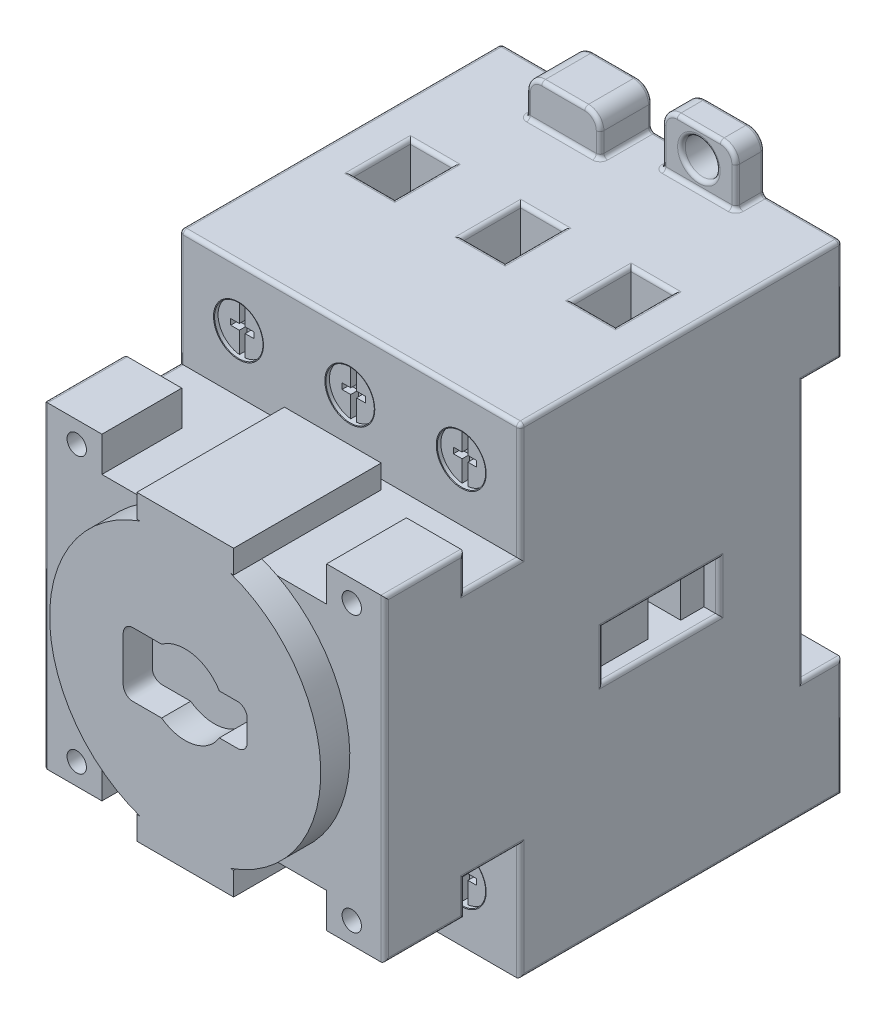
SolidWorks part; units mm, degrees
ref_plane "Front" through (0, 0, 0) normal (0, 0, 1) x (1, 0, 0)
ref_plane "Top" through (0, 0, 0) normal (0, 1, 0) x (1, 0, 0)
ref_plane "Right" through (0, 0, 0) normal (1, 0, 0) x (0, 0, -1)
sketch "Sketch1" plane through (0, 0, 0) normal (0, 0, 1) x (1, 0, 0)
  line L1 (-22.352, -31.496) -> (22.352, -31.496)
  line L2 (-22.352, -31.496) -> (-22.352, 31.496)
  line L3 (-22.352, 31.496) -> (22.352, 31.496)
  line L4 (22.352, -31.496) -> (22.352, 31.496)
  line L5 (-22.352, -31.496) -> (22.352, 31.496) construction
  line L6 (-22.352, 31.496) -> (22.352, -31.496) construction
  point P0 (0, 0)
  dimension "D1" = 44.704
  dimension "D2" = 62.992
extrude "Boss-Extrude1" add sketch "Sketch1" along normal blind 60
sketch "Sketch6" plane through (0, 0, 0) normal (0, 0, -1) x (-1, 0, 0)
  line L0 (-22.352, -31.496) -> (-22.352, 31.496) construction
  line L1 (-22.352, 18.034) -> (22.352, 18.034)
  line L2 (-22.352, 18.034) -> (-22.352, -16.002)
  line L3 (-22.352, -16.002) -> (22.352, -16.002)
  line L4 (22.352, 18.034) -> (22.352, -16.002)
  line L5 (22.352, 31.496) -> (22.352, -31.496) construction
  line L6 (-22.352, 31.496) -> (22.352, 31.496) construction
  dimension "D1" = 13.462
  dimension "D2" = 34.036
extrude "Cut-Extrude5" cut sketch "Sketch6" against normal blind 5.08
sketch "Sketch3" plane through (0, 0, 60) normal (0, 0, 1) x (1, 0, 0)
  line L0 (-22.352, 31.496) -> (-22.352, -31.496) construction
  line L1 (22.352, 20.828) -> (-22.352, 20.828)
  line L2 (22.352, 20.828) -> (22.352, 31.496)
  line L3 (22.352, 31.496) -> (-22.352, 31.496)
  line L4 (-22.352, 20.828) -> (-22.352, 31.496)
  line L5 (-22.352, -31.496) -> (22.352, -31.496)
  line L6 (-22.352, -31.496) -> (-22.352, -20.828)
  line L7 (-22.352, -20.828) -> (22.352, -20.828)
  line L8 (22.352, -31.496) -> (22.352, -20.828)
  line L9 (22.352, -31.496) -> (22.352, 31.496) construction
  dimension "D1" = 10.668
  dimension "D2" = 41.656
extrude "Cut-Extrude2" cut sketch "Sketch3" against normal blind 17.78
sketch "Sketch4" plane through (0, 0, 60) normal (0, 0, 1) x (1, 0, 0)
  line L1 (0, 0) -> (0, 0.508) construction
  circle A0 centre (0, 0.508) radius 17.78
  dimension "D1" = 35.56
  dimension "D2" = 0.508
extrude "Boss-Extrude2" add sketch "Sketch4" along normal blind 3.81
sketch "Sketch5" plane through (0, 0, 60) normal (0, 0, 1) x (1, 0, 0)
  line L0 (-22.352, 20.828) -> (22.352, 20.828) construction
  line L1 (-14.732, 16.256) -> (14.732, 16.256)
  line L2 (-14.732, 16.256) -> (-14.732, 20.828)
  line L3 (-14.732, 20.828) -> (14.732, 20.828)
  line L4 (14.732, 16.256) -> (14.732, 20.828)
  line L6 (0, 0) -> (0, 16.256) construction
  line L7 (22.352, -20.828) -> (-22.352, -20.828) construction
  line L8 (14.73, -20.828) -> (-14.73, -20.828)
  line L9 (14.73, -20.828) -> (14.73, -16.258)
  line L10 (14.73, -16.258) -> (-14.73, -16.258)
  line L11 (-14.73, -20.828) -> (-14.73, -16.258)
  line L12 (0, 0) -> (0, -16.258) construction
  dimension "D1" = 29.464
  dimension "D2" = 4.572
  dimension "D3" = 29.46
  dimension "D4" = 4.57
extrude "Cut-Extrude3" cut sketch "Sketch5" against normal blind 17.78
sketch "Sketch7" plane through (0, 0, 63.81) normal (0, 0, 1) x (1, 0, 0)
  line L0 (-5.9186, -16.258) -> (-14.73, -16.258) construction
  line L1 (-6.35, 20.32) -> (6.35, 20.32)
  line L2 (-6.35, 20.32) -> (-6.35, 17.272)
  line L3 (-6.35, 17.272) -> (6.35, 17.272)
  line L4 (6.35, 20.32) -> (6.35, 17.272)
  line L5 (6.35, -19.304) -> (-6.35, -19.304)
  line L6 (6.35, -19.304) -> (6.35, -16.258)
  line L7 (6.35, -16.258) -> (-6.35, -16.258)
  line L8 (-6.35, -19.304) -> (-6.35, -16.258)
  line L10 (0, 0) -> (0, 17.272) construction
  line L11 (0, 0) -> (0, -16.258) construction
  dimension "D1" = 3.048
  dimension "D2" = 3.046
  dimension "D3" = 12.7
  dimension "D4" = 12.7
  dimension "D5" = 17.272
extrude "Boss-Extrude3" add sketch "Sketch7" against normal up to surface (21.59 mm away) up to face at (0, 22.352, 42.22)
sketch "Sketch8" plane through (0, 20.828, 0) normal (0, 1, 0) x (1, 0, 0)
  line L0 (-22.352, -42.22) -> (-22.352, -60) construction
  line L1 (-22.352, -49.53) -> (-14.732, -49.53)
  line L2 (-22.352, -49.53) -> (-22.352, -42.22)
  line L3 (-22.352, -42.22) -> (-14.732, -42.22)
  line L4 (-14.732, -49.53) -> (-14.732, -42.22)
  line L7 (22.352, -49.53) -> (14.732, -49.53)
  line L8 (22.352, -49.53) -> (22.352, -42.22)
  line L9 (22.352, -42.22) -> (14.732, -42.22)
  line L10 (14.732, -49.53) -> (14.732, -42.22)
  line L12 (6.35, -44.45) -> (-6.35, -44.45)
  line L13 (6.35, -44.45) -> (6.35, -42.22)
  line L14 (6.35, -42.22) -> (-6.35, -42.22)
  line L15 (-6.35, -44.45) -> (-6.35, -42.22)
  line L16 (6.35, -42.22) -> (6.35, -63.81) construction
  line L17 (22.352, -42.22) -> (22.352, 0) construction
  dimension "D1" = 7.31
  dimension "D2" = 2.23
  dimension "D3" = 7.31
extrude "Cut-Extrude6" cut sketch "Sketch8" against normal up to surface (4.572 mm away) up to face at (0, 16.256, 54.0733)
sketch "Sketch9" plane through (0, 0, 63.81) normal (0, 0, 1) x (1, 0, 0)
  line L10 (-5.9186, -16.258) -> (-6.35, -16.258)
  line L11 (-6.35, -16.258) -> (-6.35, -19.304)
  line L12 (-6.35, -19.304) -> (6.35, -19.304)
  line L13 (6.35, -19.304) -> (6.35, -16.258)
  line L14 (6.35, -16.258) -> (5.9186, -16.258)
  line L15 (5.9242, 17.272) -> (6.35, 17.272)
  line L16 (6.35, 17.272) -> (6.35, 20.32)
  line L17 (6.35, 20.32) -> (-6.35, 20.32)
  line L18 (-6.35, 20.32) -> (-6.35, 17.272)
  line L19 (-6.35, 17.272) -> (-5.9242, 17.272)
  line L20 (-5.9186, -16.258) -> (-6.35, -16.258)
  line L21 (-6.35, -16.258) -> (-6.35, -19.304)
  line L22 (-6.35, -19.304) -> (6.35, -19.304)
  line L23 (6.35, -19.304) -> (6.35, -16.258)
  line L24 (6.35, -16.258) -> (5.9186, -16.258)
  line L25 (5.9242, 17.272) -> (6.35, 17.272)
  line L26 (6.35, 17.272) -> (6.35, 20.32)
  line L27 (6.35, 20.32) -> (-6.35, 20.32)
  line L28 (-6.35, 20.32) -> (-6.35, 17.272)
  line L29 (-6.35, 17.272) -> (-5.9242, 17.272)
  arc A2 (-5.9242, 17.272) -> (-5.9186, -16.258) centre (0, 0.508) ccw
  arc A3 (5.9186, -16.258) -> (5.9242, 17.272) centre (0, 0.508) ccw
  arc A4 (-5.9242, 17.272) -> (-5.9186, -16.258) centre (0, 0.508) ccw
  arc A5 (5.9186, -16.258) -> (5.9242, 17.272) centre (0, 0.508) ccw
  arc A6 (-3.09, -3.683) -> (4.4721, -2.159) centre (0, 0.508) ccw
  arc A7 (4.4721, 3.175) -> (-3.09, 4.699) centre (0, 0.508) ccw
  spline S2 degree 3 poles (-3.09, 4.699) (-4.346, 4.699) (-5.602, 4.699) (-6.858, 4.699) (-7.6019, 4.699) (-8.128, 4.1729) (-8.128, 3.429) (-8.128, 1.4817) (-8.128, -0.4657) (-8.128, -2.413) (-8.128, -3.1569) (-7.6019, -3.683) (-6.858, -3.683) (-5.602, -3.683) (-4.346, -3.683) (-3.09, -3.683) knots 0.43328 0.43328 0.43328 0.43328 0.519787 0.519787 0.519787 0.561023 0.561023 0.561023 0.695148 0.695148 0.695148 0.736383 0.736383 0.736383 0.822891 0.822891 0.822891 0.822891 weights 1 1 1 1 0.804738 0.804738 1 1 1 1 0.804738 0.804738 1 1 1 1
  spline S3 degree 3 poles (4.4721, -2.159) (5.2674, -2.159) (6.0627, -2.159) (6.858, -2.159) (7.6019, -2.159) (8.128, -1.6329) (8.128, -0.889) (8.128, 0.0423) (8.128, 0.9737) (8.128, 1.905) (8.128, 2.6489) (7.6019, 3.175) (6.858, 3.175) (6.0627, 3.175) (5.2674, 3.175) (4.4721, 3.175) knots 0 0 0 0 0.054777 0.054777 0.054777 0.096012 0.096012 0.096012 0.160159 0.160159 0.160159 0.201394 0.201394 0.201394 0.256171 0.256171 0.256171 0.256171 weights 1 1 1 1 0.804738 0.804738 1 1 1 1 0.804738 0.804738 1 1 1 1
  dimension "D1" = 0
extrude "Cut-Extrude7" cut sketch "Sketch9" against normal up to surface (3.81 mm away) contours A6 S3 A7 S2 up to face at (14.9776, -1.8919, 60)
sketch "Sketch10" plane through (0, 0, 0) normal (0, 0, -1) x (-1, 0, 0)
  line L0 (-22.352, 31.496) -> (22.352, 31.496) construction
  line L1 (-12.192, 31.496) -> (-2.54, 31.496)
  line L2 (-12.192, 31.496) -> (-12.192, 38.608)
  line L3 (-12.192, 38.608) -> (-2.54, 38.608)
  line L4 (-2.54, 31.496) -> (-2.54, 38.608)
  line L7 (2.54, 36.576) -> (12.192, 36.576)
  line L8 (2.54, 36.576) -> (2.54, 31.496)
  line L9 (2.54, 31.496) -> (12.192, 31.496)
  line L10 (12.192, 36.576) -> (12.192, 31.496)
  line L11 (22.352, -31.496) -> (-22.352, -31.496) construction
  line L12 (12.7, -38.608) -> (3.048, -38.608)
  line L13 (12.7, -38.608) -> (12.7, -31.496)
  line L14 (12.7, -31.496) -> (3.048, -31.496)
  line L15 (3.048, -38.608) -> (3.048, -31.496)
  line L17 (-22.352, 18.034) -> (-22.352, 31.496) construction
  line L18 (-22.352, -31.496) -> (-22.352, -16.002) construction
  dimension "D1" = 10.16
  dimension "D2" = 9.652
  dimension "D3" = 5.08
  dimension "D4" = 9.652
  dimension "D5" = 7.112
  dimension "D6" = 5.08
  dimension "D7" = 25.4
  dimension "D8" = 9.652
  dimension "D9" = 7.112
extrude "Boss-Extrude4" add sketch "Sketch10" against normal blind 6.858
sketch "Sketch11" plane through (0, 0, 6.858) normal (0, 0, 1) x (1, 0, 0)
  line L0 (12.192, 31.496) -> (12.192, 38.608) construction
  line L1 (12.192, 38.608) -> (2.54, 38.608) construction
  line L2 (2.54, 38.608) -> (2.54, 31.496) construction
  line L3 (2.54, 31.496) -> (12.192, 31.496) construction
  line L4 (-12.7, -31.496) -> (-12.7, -38.608) construction
  line L5 (-12.7, -38.608) -> (-3.048, -38.608) construction
  line L6 (-3.048, -38.608) -> (-3.048, -31.496) construction
  line L7 (-3.048, -31.496) -> (-12.7, -31.496) construction
  line L8 (12.192, 31.496) -> (12.192, 38.608)
  line L9 (12.192, 38.608) -> (2.54, 38.608)
  line L10 (2.54, 38.608) -> (2.54, 31.496)
  line L11 (2.54, 31.496) -> (12.192, 31.496)
  line L12 (-12.7, -31.496) -> (-12.7, -38.608)
  line L13 (-12.7, -38.608) -> (-3.048, -38.608)
  line L14 (-3.048, -38.608) -> (-3.048, -31.496)
  line L15 (-3.048, -31.496) -> (-12.7, -31.496)
extrude "Cut-Extrude8" cut sketch "Sketch11" against normal offset from surface (3.048 mm away) 3.81 up to face at (1.0583, 31.2843, 0)
sketch "Sketch12" plane through (0, 0, 0) normal (0, 0, -1) x (-1, 0, 0)
  circle A0 centre (-7.366, 35.052) radius 2.286
  circle A1 centre (7.874, -35.052) radius 2.286
  dimension "D1" = 4.572
  dimension "D2" = 4.572
  dimension "D3" = 35.052
  dimension "D4" = 7.366
  dimension "D5" = 7.874
  dimension "D6" = 35.052
extrude "Cut-Extrude9" cut sketch "Sketch12" against normal through all
sketch "Sketch14" plane through (0, 0, 42.22) normal (0, 0, 1) x (1, 0, 0)
  line L60 (-14.224, -23.368) -> (-14.224, -20.5969)
  line L61 (-13.081, -23.368) -> (-14.224, -23.368)
  line L62 (-13.081, -24.13) -> (-13.081, -23.368)
  line L63 (-14.224, -24.13) -> (-13.081, -24.13)
  line L64 (-14.224, -26.9011) -> (-14.224, -24.13)
  line L65 (-14.986, -24.13) -> (-14.986, -26.9011)
  line L66 (-16.129, -24.13) -> (-14.986, -24.13)
  line L67 (-16.129, -23.368) -> (-16.129, -24.13)
  line L68 (-14.986, -23.368) -> (-16.129, -23.368)
  line L69 (-14.986, -20.5969) -> (-14.986, -23.368)
  line L70 (0.381, -23.368) -> (0.381, -20.5969)
  line L71 (1.524, -23.368) -> (0.381, -23.368)
  line L72 (1.524, -24.13) -> (1.524, -23.368)
  line L73 (0.381, -24.13) -> (1.524, -24.13)
  line L74 (0.381, -26.9011) -> (0.381, -24.13)
  line L75 (-0.381, -24.13) -> (-0.381, -26.9011)
  line L76 (-1.524, -24.13) -> (-0.381, -24.13)
  line L77 (-1.524, -23.368) -> (-1.524, -24.13)
  line L78 (-0.381, -23.368) -> (-1.524, -23.368)
  line L79 (-0.381, -20.5969) -> (-0.381, -23.368)
  line L80 (14.986, -24.13) -> (14.986, -26.9011)
  line L81 (16.129, -24.13) -> (14.986, -24.13)
  line L82 (16.129, -23.368) -> (16.129, -24.13)
  line L83 (14.986, -23.368) -> (16.129, -23.368)
  line L84 (14.986, -20.5969) -> (14.986, -23.368)
  line L85 (14.224, -23.368) -> (14.224, -20.5969)
  line L86 (13.081, -23.368) -> (14.224, -23.368)
  line L87 (13.081, -24.13) -> (13.081, -23.368)
  line L88 (14.224, -24.13) -> (13.081, -24.13)
  line L89 (14.224, -26.9011) -> (14.224, -24.13)
  line L90 (14.986, 24.13) -> (14.986, 26.9011)
  line L91 (16.129, 24.13) -> (14.986, 24.13)
  line L92 (16.129, 23.368) -> (16.129, 24.13)
  line L93 (14.986, 23.368) -> (16.129, 23.368)
  line L94 (14.986, 20.5969) -> (14.986, 23.368)
  line L95 (14.224, 23.368) -> (14.224, 20.5969)
  line L96 (13.081, 23.368) -> (14.224, 23.368)
  line L97 (13.081, 24.13) -> (13.081, 23.368)
  line L98 (14.224, 24.13) -> (13.081, 24.13)
  line L99 (14.224, 26.9011) -> (14.224, 24.13)
  line L100 (0.381, 23.368) -> (0.381, 20.5969)
  line L101 (1.524, 23.368) -> (0.381, 23.368)
  line L102 (1.524, 24.13) -> (1.524, 23.368)
  line L103 (0.381, 24.13) -> (1.524, 24.13)
  line L104 (0.381, 26.9011) -> (0.381, 24.13)
  line L105 (-0.381, 24.13) -> (-0.381, 26.9011)
  line L106 (-1.524, 24.13) -> (-0.381, 24.13)
  line L107 (-1.524, 23.368) -> (-1.524, 24.13)
  line L108 (-0.381, 23.368) -> (-1.524, 23.368)
  line L109 (-0.381, 20.5969) -> (-0.381, 23.368)
  line L110 (-14.224, 23.368) -> (-14.224, 20.5969)
  line L111 (-13.081, 23.368) -> (-14.224, 23.368)
  line L112 (-13.081, 24.13) -> (-13.081, 23.368)
  line L113 (-14.224, 24.13) -> (-13.081, 24.13)
  line L114 (-14.224, 26.9011) -> (-14.224, 24.13)
  line L115 (-14.986, 24.13) -> (-14.986, 26.9011)
  line L116 (-16.129, 24.13) -> (-14.986, 24.13)
  line L117 (-16.129, 23.368) -> (-16.129, 24.13)
  line L118 (-14.986, 23.368) -> (-16.129, 23.368)
  line L119 (-14.986, 20.5969) -> (-14.986, 23.368)
  line L128 (22.352, -31.496) -> (22.352, 31.496)
  line L129 (22.352, 31.496) -> (-22.352, 31.496)
  line L130 (-22.352, 31.496) -> (-22.352, -31.496)
  line L131 (-22.352, -31.496) -> (22.352, -31.496)
  arc A12 (-17.78, -23.749) -> (-11.43, -23.749) centre (-14.605, -23.749) ccw
  arc A13 (-11.43, -23.749) -> (-17.78, -23.749) centre (-14.605, -23.749) ccw
  arc A14 (-3.175, -23.749) -> (3.175, -23.749) centre (0, -23.749) ccw
  arc A15 (3.175, -23.749) -> (-3.175, -23.749) centre (0, -23.749) ccw
  arc A16 (11.43, -23.749) -> (17.78, -23.749) centre (14.605, -23.749) ccw
  arc A17 (17.78, -23.749) -> (11.43, -23.749) centre (14.605, -23.749) ccw
  arc A18 (11.43, 23.749) -> (17.78, 23.749) centre (14.605, 23.749) ccw
  arc A19 (17.78, 23.749) -> (11.43, 23.749) centre (14.605, 23.749) ccw
  arc A20 (-3.175, 23.749) -> (3.175, 23.749) centre (0, 23.749) ccw
  arc A21 (3.175, 23.749) -> (-3.175, 23.749) centre (0, 23.749) ccw
  arc A22 (-17.78, 23.749) -> (-11.43, 23.749) centre (-14.605, 23.749) ccw
  arc A23 (-11.43, 23.749) -> (-17.78, 23.749) centre (-14.605, 23.749) ccw
  line M10 (-14.73, -16.258) -> (-14.73, -20.828)
  line M11 (-14.73, -20.828) -> (-22.352, -20.828)
  line M15 (22.352, -20.828) -> (14.73, -20.828)
  line M16 (14.73, -20.828) -> (14.73, -16.258)
extrude "Cut-Extrude11" cut sketch "Sketch14" against normal blind 1.5 contours L114 A23 L115 L116 L117 L118 L119 A22 L110 L111 L112 L113 | L104 A21 L105 L106 L107 L108 L109 A20 L100 L101 L102 L103 | L90 A19 L99 L98 L97 L96 L95 A18 L94 L93 L92 L91 | A17 L85 L86 L87 L88 L89 A16 L80 L81 L82 L83 L84 M16 M15 | L70 A15 L79 L78 L77 L76 L75 A14 L74 L73 L72 L71 | L60 A13 L69 L68 L67 L66 L65 A12 L64 L63 L62 L61 M10 M11
sketch "Sketch15" plane through (0, -20.828, 0) normal (0, -1, 0) x (1, 0, 0)
  line L1 (14.73, 42.22) -> (14.73, 60) construction
  line L2 (22.352, 42.22) -> (14.73, 42.22)
  line L3 (22.352, 42.22) -> (22.352, 49.53)
  line L4 (22.352, 49.53) -> (14.73, 49.53)
  line L7 (-14.73, 40.72) -> (-14.73, 60) construction
  line L8 (-22.352, 42.22) -> (-14.73, 42.22)
  line L9 (-22.352, 42.22) -> (-22.352, 49.53)
  line L10 (-22.352, 49.53) -> (-14.73, 49.53)
  line L13 (-6.35, 42.22) -> (-6.35, 60) construction
  line L14 (6.35, 42.22) -> (-6.35, 42.22)
  line L15 (6.35, 42.22) -> (6.35, 44.25)
  line L16 (6.35, 44.25) -> (-6.35, 44.25)
  line L19 (-14.73, 42.22) -> (-14.73, 49.53)
  line L20 (14.73, 42.22) -> (14.73, 49.53)
  line L21 (-6.35, 42.22) -> (-6.35, 44.25)
  dimension "D1" = 2.03
  dimension "D2" = 7.31
  dimension "D3" = 7.31
extrude "Cut-Extrude12" cut sketch "Sketch15" against normal up to surface (4.57 mm away) up to face at (10.54, -16.258, 51.11)
sketch "Sketch13" plane through (0, 0, 60) normal (0, 0, 1) x (1, 0, 0)
  line L0 (-22.352, 18.034) -> (22.352, 18.034) construction
  line L2 (-18.034, 18.034) -> (18.034, 18.034) construction
  line L3 (0, 0) -> (0, 18.034) construction
  line L4 (-18.034, -18.034) -> (18.034, -18.034) construction
  line L5 (0, -18.034) -> (0, 0) construction
  circle A0 centre (-18.034, 18.034) radius 1.27
  circle A1 centre (18.034, 18.034) radius 1.27
  circle A2 centre (18.034, -18.034) radius 1.27
  circle A3 centre (-18.034, -18.034) radius 1.27
  dimension "D1" = 2.54
  dimension "D2" = 2.54
  dimension "D3" = 2.54
  dimension "D4" = 2.54
  dimension "D5" = 36.068
  dimension "D6" = 36.068
  dimension "D7" = 18.034
extrude "Cut-Extrude10" cut sketch "Sketch13" against normal up to next
sketch "Sketch16" plane through (0, -31.496, 0) normal (0, -1, 0) x (1, 0, 0)
  line L0 (-22.352, 0) -> (-12.7, 0) construction
  line L1 (11.684, 24.638) -> (17.272, 24.638)
  line L2 (11.684, 24.638) -> (11.684, 17.018)
  line L3 (11.684, 17.018) -> (17.272, 17.018)
  line L4 (17.272, 24.638) -> (17.272, 17.018)
  line L5 (-2.794, 24.638) -> (2.794, 24.638)
  line L6 (-2.794, 24.638) -> (-2.794, 17.018)
  line L7 (-2.794, 17.018) -> (2.794, 17.018)
  line L8 (2.794, 24.638) -> (2.794, 17.018)
  line L9 (-17.272, 24.638) -> (-11.684, 24.638)
  line L10 (-17.272, 24.638) -> (-17.272, 17.018)
  line L11 (-17.272, 17.018) -> (-11.684, 17.018)
  line L12 (-11.684, 24.638) -> (-11.684, 17.018)
  line L13 (-3.048, 0) -> (22.352, 0) construction
  line L14 (-22.352, 42.22) -> (-22.352, 0) construction
  point P22 (-22.352, 21.11)
  dimension "D1" = 17.018
  dimension "D2" = 17.018
  dimension "D3" = 17.018
  dimension "D4" = 5.08
  dimension "D5" = 7.62
  dimension "D6" = 7.62
  dimension "D7" = 7.62
  dimension "D8" = 5.588
  dimension "D9" = 5.588
  dimension "D10" = 8.89
  dimension "D11" = 8.89
  dimension "D12" = 5.588
extrude "Cut-Extrude13" cut sketch "Sketch16" against normal blind 10
sketch "Sketch17" plane through (0, 31.496, 0) normal (0, 1, 0) x (1, 0, 0)
  line L0 (-12.192, 0) -> (-22.352, 0) construction
  line L1 (-11.684, -24.638) -> (-17.272, -24.638)
  line L2 (-11.684, -24.638) -> (-11.684, -17.018)
  line L3 (-11.684, -17.018) -> (-17.272, -17.018)
  line L4 (-17.272, -24.638) -> (-17.272, -17.018)
  line L5 (2.794, -24.638) -> (-2.794, -24.638)
  line L6 (2.794, -24.638) -> (2.794, -17.018)
  line L7 (2.794, -17.018) -> (-2.794, -17.018)
  line L8 (-2.794, -24.638) -> (-2.794, -17.018)
  line L9 (17.272, -24.638) -> (11.684, -24.638)
  line L10 (17.272, -24.638) -> (17.272, -17.018)
  line L11 (17.272, -17.018) -> (11.684, -17.018)
  line L12 (11.684, -24.638) -> (11.684, -17.018)
  line L13 (2.54, 0) -> (12.192, 0) construction
  line L14 (22.352, 0) -> (12.192, 0) construction
  line L15 (-22.352, -42.22) -> (-22.352, 0) construction
  dimension "D1" = 17.018
  dimension "D2" = 17.018
  dimension "D3" = 17.018
  dimension "D4" = 5.08
  dimension "D5" = 5.588
  dimension "D6" = 8.89
  dimension "D7" = 5.588
  dimension "D8" = 8.89
  dimension "D9" = 5.588
  dimension "D10" = 7.62
  dimension "D11" = 7.62
  dimension "D12" = 7.62
extrude "Cut-Extrude14" cut sketch "Sketch17" against normal blind 10
sketch "Sketch20" plane through (0, 0, 42.22) normal (0, 0, 1) x (1, 0, 0)
  line L0 (-14.224, -23.368) -> (-14.224, -20.5969)
  line L1 (-13.081, -23.368) -> (-14.224, -23.368)
  line L2 (-13.081, -24.13) -> (-13.081, -23.368)
  line L3 (-14.224, -24.13) -> (-13.081, -24.13)
  line L4 (-14.224, -26.9011) -> (-14.224, -24.13)
  line L5 (-14.986, -24.13) -> (-14.986, -26.9011)
  line L6 (-16.129, -24.13) -> (-14.986, -24.13)
  line L7 (-16.129, -23.368) -> (-16.129, -24.13)
  line L8 (-14.986, -23.368) -> (-16.129, -23.368)
  line L9 (-14.986, -20.5969) -> (-14.986, -23.368)
  line L10 (0.381, -23.368) -> (0.381, -20.5969)
  line L11 (1.524, -23.368) -> (0.381, -23.368)
  line L12 (1.524, -24.13) -> (1.524, -23.368)
  line L13 (0.381, -24.13) -> (1.524, -24.13)
  line L14 (0.381, -26.9011) -> (0.381, -24.13)
  line L15 (-0.381, -24.13) -> (-0.381, -26.9011)
  line L16 (-1.524, -24.13) -> (-0.381, -24.13)
  line L17 (-1.524, -23.368) -> (-1.524, -24.13)
  line L18 (-0.381, -23.368) -> (-1.524, -23.368)
  line L19 (-0.381, -20.5969) -> (-0.381, -23.368)
  line L20 (14.986, -24.13) -> (14.986, -26.9011)
  line L21 (16.129, -24.13) -> (14.986, -24.13)
  line L22 (16.129, -23.368) -> (16.129, -24.13)
  line L23 (14.986, -23.368) -> (16.129, -23.368)
  line L24 (14.986, -20.5969) -> (14.986, -23.368)
  line L25 (14.224, -23.368) -> (14.224, -20.5969)
  line L26 (13.081, -23.368) -> (14.224, -23.368)
  line L27 (13.081, -24.13) -> (13.081, -23.368)
  line L28 (14.224, -24.13) -> (13.081, -24.13)
  line L29 (14.224, -26.9011) -> (14.224, -24.13)
  line L30 (14.986, 24.13) -> (14.986, 26.9011)
  line L31 (16.129, 24.13) -> (14.986, 24.13)
  line L32 (16.129, 23.368) -> (16.129, 24.13)
  line L33 (14.986, 23.368) -> (16.129, 23.368)
  line L34 (14.986, 20.5969) -> (14.986, 23.368)
  line L35 (14.224, 23.368) -> (14.224, 20.5969)
  line L36 (13.081, 23.368) -> (14.224, 23.368)
  line L37 (13.081, 24.13) -> (13.081, 23.368)
  line L38 (14.224, 24.13) -> (13.081, 24.13)
  line L39 (14.224, 26.9011) -> (14.224, 24.13)
  line L40 (0.381, 23.368) -> (0.381, 20.5969)
  line L41 (1.524, 23.368) -> (0.381, 23.368)
  line L42 (1.524, 24.13) -> (1.524, 23.368)
  line L43 (0.381, 24.13) -> (1.524, 24.13)
  line L44 (0.381, 26.9011) -> (0.381, 24.13)
  line L45 (-0.381, 24.13) -> (-0.381, 26.9011)
  line L46 (-1.524, 24.13) -> (-0.381, 24.13)
  line L47 (-1.524, 23.368) -> (-1.524, 24.13)
  line L48 (-0.381, 23.368) -> (-1.524, 23.368)
  line L49 (-0.381, 20.5969) -> (-0.381, 23.368)
  line L50 (-14.224, 23.368) -> (-14.224, 20.5969)
  line L51 (-13.081, 23.368) -> (-14.224, 23.368)
  line L52 (-13.081, 24.13) -> (-13.081, 23.368)
  line L53 (-14.224, 24.13) -> (-13.081, 24.13)
  line L54 (-14.224, 26.9011) -> (-14.224, 24.13)
  line L55 (-14.986, 24.13) -> (-14.986, 26.9011)
  line L56 (-16.129, 24.13) -> (-14.986, 24.13)
  line L57 (-16.129, 23.368) -> (-16.129, 24.13)
  line L58 (-14.986, 23.368) -> (-16.129, 23.368)
  line L59 (-14.986, 20.5969) -> (-14.986, 23.368)
  line L60 (22.352, -31.496) -> (22.352, 31.496)
  line L61 (22.352, 31.496) -> (-22.352, 31.496)
  line L62 (-22.352, 31.496) -> (-22.352, -31.496)
  line L63 (-22.352, -31.496) -> (22.352, -31.496)
  arc A0 (-17.78, -23.749) -> (-11.43, -23.749) centre (-14.605, -23.749) ccw
  arc A1 (-11.43, -23.749) -> (-17.78, -23.749) centre (-14.605, -23.749) ccw
  arc A2 (-3.175, -23.749) -> (3.175, -23.749) centre (0, -23.749) ccw
  arc A3 (3.175, -23.749) -> (-3.175, -23.749) centre (0, -23.749) ccw
  arc A4 (11.43, -23.749) -> (17.78, -23.749) centre (14.605, -23.749) ccw
  arc A5 (17.78, -23.749) -> (11.43, -23.749) centre (14.605, -23.749) ccw
  arc A6 (11.43, 23.749) -> (17.78, 23.749) centre (14.605, 23.749) ccw
  arc A7 (17.78, 23.749) -> (11.43, 23.749) centre (14.605, 23.749) ccw
  arc A8 (-3.175, 23.749) -> (3.175, 23.749) centre (0, 23.749) ccw
  arc A9 (3.175, 23.749) -> (-3.175, 23.749) centre (0, 23.749) ccw
  arc A10 (-17.78, 23.749) -> (-11.43, 23.749) centre (-14.605, 23.749) ccw
  arc A11 (-11.43, 23.749) -> (-17.78, 23.749) centre (-14.605, 23.749) ccw
  line M1 (14.986, 26.9011) -> (14.986, 24.13)
  line M2 (14.986, 24.13) -> (16.129, 24.13)
  line M3 (16.129, 24.13) -> (16.129, 23.368)
  line M4 (16.129, 23.368) -> (14.986, 23.368)
  line M5 (14.986, 23.368) -> (14.986, 20.5969)
  line M7 (14.224, 20.5969) -> (14.224, 23.368)
  line M8 (14.224, 23.368) -> (13.081, 23.368)
  line M9 (13.081, 23.368) -> (13.081, 24.13)
  line M10 (13.081, 24.13) -> (14.224, 24.13)
  line M11 (14.224, 24.13) -> (14.224, 26.9011)
  line M18 (-14.224, 26.9011) -> (-14.224, 24.13)
  line M19 (-14.224, 24.13) -> (-13.081, 24.13)
  line M20 (-13.081, 24.13) -> (-13.081, 23.368)
  line M21 (-13.081, 23.368) -> (-14.224, 23.368)
  line M22 (-14.224, 23.368) -> (-14.224, 20.5969)
  line M24 (-14.986, 20.5969) -> (-14.986, 23.368)
  line M25 (-14.986, 23.368) -> (-16.129, 23.368)
  line M26 (-16.129, 23.368) -> (-16.129, 24.13)
  line M27 (-16.129, 24.13) -> (-14.986, 24.13)
  line M28 (-14.986, 24.13) -> (-14.986, 26.9011)
  line M30 (0.381, 26.9011) -> (0.381, 24.13)
  line M31 (0.381, 24.13) -> (1.524, 24.13)
  line M32 (1.524, 24.13) -> (1.524, 23.368)
  line M33 (1.524, 23.368) -> (0.381, 23.368)
  line M34 (0.381, 23.368) -> (0.381, 20.5969)
  line M36 (-0.381, 20.5969) -> (-0.381, 23.368)
  line M37 (-0.381, 23.368) -> (-1.524, 23.368)
  line M38 (-1.524, 23.368) -> (-1.524, 24.13)
  line M39 (-1.524, 24.13) -> (-0.381, 24.13)
  line M40 (-0.381, 24.13) -> (-0.381, 26.9011)
extrude "Cut-Extrude15" cut sketch "Sketch20" against normal blind 0.5 contours A11 A10 M28 M24 M25 M26 M27 | A10 A11 M18 M19 M20 M21 M22 | A9 A8 M40 M36 M37 M38 M39 | A8 A9 M30 M31 M32 M33 M34 | A7 A6 M11 M7 M8 M9 M10 | A6 A7 M1 M2 M3 M4 M5 | A4 A5 L24 L23 L22 L21 L20 | L25 A5 A4 L29 L28 L27 L26 | A2 A3 L10 L11 L12 L13 L14 | L19 A3 A2 L15 L16 L17 L18 | A0 A1 L0 L1 L2 L3 L4 | L9 A1 A0 L5 L6 L7 L8
sketch "Sketch21" plane through (-22.352, 0, 0) normal (-1, 0, 0) x (0, 0, 1)
  line L0 (0, 31.496) -> (0, 18.034) construction
  line L1 (16.129, 3.175) -> (31.369, 3.175)
  line L2 (16.129, 3.175) -> (16.129, -3.175)
  line L3 (16.129, -3.175) -> (31.369, -3.175)
  line L4 (31.369, 3.175) -> (31.369, -3.175)
  dimension "D1" = 16.129
  dimension "D2" = 15.24
  dimension "D3" = 6.35
  dimension "D4" = 3.175
extrude "Cut-Extrude16" cut sketch "Sketch21" against normal blind 2
sketch "Sketch22" plane through (22.352, 0, 0) normal (1, 0, 0) x (0, 0, -1)
  line L1 (-31.369, 3.175) -> (-16.129, 3.175)
  line L2 (-31.369, 3.175) -> (-31.369, -3.175)
  line L3 (-31.369, -3.175) -> (-16.129, -3.175)
  line L4 (-16.129, 3.175) -> (-16.129, -3.175)
  dimension "D1" = 16.129
  dimension "D2" = 15.24
  dimension "D3" = 6.35
  dimension "D4" = 3.175
extrude "Cut-Extrude17" cut sketch "Sketch22" against normal blind 2
sketch "Sketch24" plane through (-22.352, 0, 0) normal (-1, 0, 0) x (0, 0, 1)
  line L1 (19.177, 3.175) -> (23.495, 3.175)
  line L2 (19.177, 3.175) -> (19.177, -3.175)
  line L3 (19.177, -3.175) -> (23.495, -3.175)
  line L4 (23.495, 3.175) -> (23.495, -3.175)
  line L5 (16.129, -3.175) -> (31.369, -3.175) construction
  line L7 (16.129, 3.175) -> (16.129, -3.175) construction
  line L8 (31.369, 3.175) -> (16.129, 3.175) construction
  dimension "D1" = 3.048
  dimension "D2" = 4.318
extrude "Cut-Extrude18" cut sketch "Sketch24" against normal blind 10
sketch "Sketch25" plane through (22.352, 0, 0) normal (1, 0, 0) x (0, 0, -1)
  line L1 (-23.495, 3.175) -> (-19.177, 3.175)
  line L2 (-23.495, 3.175) -> (-23.495, -3.175)
  line L3 (-23.495, -3.175) -> (-19.177, -3.175)
  line L4 (-19.177, 3.175) -> (-19.177, -3.175)
  line L5 (-31.369, -3.175) -> (-16.129, -3.175) construction
  line L7 (-16.129, -3.175) -> (-16.129, 3.175) construction
  line L8 (-16.129, 3.175) -> (-31.369, 3.175) construction
  dimension "D1" = 3.048
  dimension "D2" = 4.318
extrude "Cut-Extrude19" cut sketch "Sketch25" against normal blind 10
fillet "Fillet1" radius 2 6 edges at (-12.7, -38.608, 1.905) (-3.048, -38.608, 1.905) (-12.192, 36.576, 3.429) (-2.54, 36.576, 3.429) (2.54, 38.608, 1.905) (12.192, 38.608, 1.905)
fillet "Fillet2" radius 0.5 92 edges at (-7.366, 36.576, 0) (-7.366, 36.576, 6.858) (7.366, 38.608, 0) (7.366, 38.608, 3.81) (11.6062, 38.0222, 0) (-11.6062, 35.9902, 0) (-3.1258, 35.9902, 0) (3.1258, 38.0222, 0) (12.192, 34.052, 3.81) (-12.192, 33.036, 6.858) (-12.192, 33.036, 0) (-2.54, 33.036, 0) (-2.54, 33.036, 6.858) (2.54, 34.052, 3.81) (-22.352, -31.496, 21.11) (-22.352, -23.749, 0) (-22.352, -16.002, 2.54) (-22.352, 1.016, 5.08) (-22.352, 18.034, 2.54) (-22.352, 24.765, 0) (-22.352, 23.876, 42.22) (-22.352, 16.256, 45.875) (-22.352, 18.542, 49.53) (-22.352, 20.828, 54.765) (-22.352, 0, 60) (-22.352, -20.828, 54.765) (-22.352, -18.543, 49.53) (-22.352, -16.258, 45.875) (-22.352, -23.877, 42.22) (-22.352, 0, 31.369) (-22.352, 3.175, 23.749) (-22.352, 0, 16.129) (-22.352, -3.175, 23.749) (22.352, 0, 60) (22.352, 20.828, 54.765) (22.352, 18.542, 49.53) (22.352, 16.256, 45.875) (22.352, 23.876, 42.22) (22.352, 24.765, 0) (22.352, 18.034, 2.54) (22.352, 1.016, 5.08) (22.352, -16.002, 2.54) (22.352, -23.749, 0) (22.352, -31.496, 21.11) (22.352, -23.877, 42.22) (22.352, -16.258, 45.875) (22.352, -18.543, 49.53) (22.352, -20.828, 54.765) (22.352, 0, 16.129) (22.352, 3.175, 23.749) (22.352, 0, 31.369) (22.352, -3.175, 23.749) (22.352, 31.496, 21.11) (0, 31.496, 42.22) (-22.352, 31.496, 21.11) (-12.192, 31.496, 3.429) (-7.366, 31.496, 6.858) (-2.54, 31.496, 3.429) (7.366, 31.496, 3.81) (-17.272, 31.496, 20.828) (-14.478, 31.496, 24.638) (-11.684, 31.496, 20.828) (-14.478, 31.496, 17.018) (-2.794, 31.496, 20.828) (0, 31.496, 24.638) (2.794, 31.496, 20.828) (0, 31.496, 17.018) (11.684, 31.496, 20.828) (14.478, 31.496, 24.638) (17.272, 31.496, 20.828) (14.478, 31.496, 17.018) (-7.874, -31.496, 3.81) (-3.048, -34.052, 3.81) (-3.6338, -38.0222, 3.81) (-7.874, -38.608, 3.81) (-12.1142, -38.0222, 3.81) (-12.7, -34.052, 3.81) (-10.16, -35.052, 3.81) (11.6062, 38.0222, 3.81) (3.1258, 38.0222, 3.81) (5.08, 35.052, 3.81) (-3.1258, 35.9902, 6.858) (-11.6062, 35.9902, 6.858)
chamfer "Chamfer1" distance 0.1 angle 20 6 edges at (17.78, 23.749, 42.22) (3.175, 23.749, 42.22) (-11.43, 23.749, 42.22) (14.3518, -26.9139, 42.22) (3.175, -23.749, 42.22) (-14.3518, -26.9139, 42.22)
